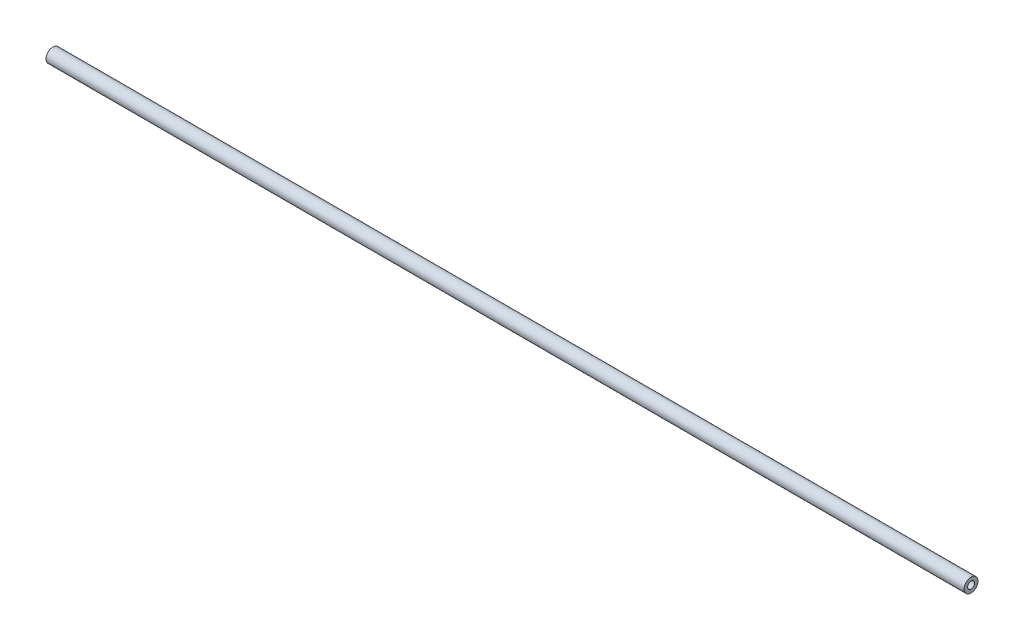
SolidWorks part; units mm, degrees
material "1060-H18"
ref_plane "Front Plane" through (0, 0, 0) normal (0, 0, 1) x (1, 0, 0)
ref_plane "Top Plane" through (0, 0, 0) normal (0, 1, 0) x (1, 0, 0)
ref_plane "Right Plane" through (0, 0, 0) normal (1, 0, 0) x (0, 0, -1)
sketch "Sketch2" plane through (0, 0, 0) normal (1, 0, 0) x (0, 0, -1)
  circle A0 centre (0, 0) radius 6.35
  circle A1 centre (0, 0) radius 3.175
  dimension "D1" = 12.7
  dimension "D2" = 6.35
extrude "Boss-Extrude2" add sketch "Sketch2" along normal blind 841.1766
equation "\"E\"= 10 * 10 ^ 6'Mod of Elasticity"
equation "\"Di\"= .25in'Inner Dia"
equation "\"Do\"= .5in'Outer Dia"
equation "\"t\"= ( ( \"Do\" - \"Di\" ) / 2 )'Wall Thickness"
equation "\"def\"= .009in'Max Axial Deflection"
equation "\"Area\"= ( 3.14 / 4 ) * ( \"Do\" ^ 2 - \"Di\" ^ 2 )'Area"
equation "\"F\"= 400'Load"
equation "\"Length\"= ( \"def\" * \"Area\" * \"E\" ) / ( \"F\" )'Min length"
equation "\"Axial Stress\"= \"F\" / \"Area\"'PSI"
equation "\"D1@Sketch2\"=\"Do\""
equation "\"D2@Sketch2\"=\"Di\""
equation "\"D1@Boss-Extrude2\"=\"Length\""
